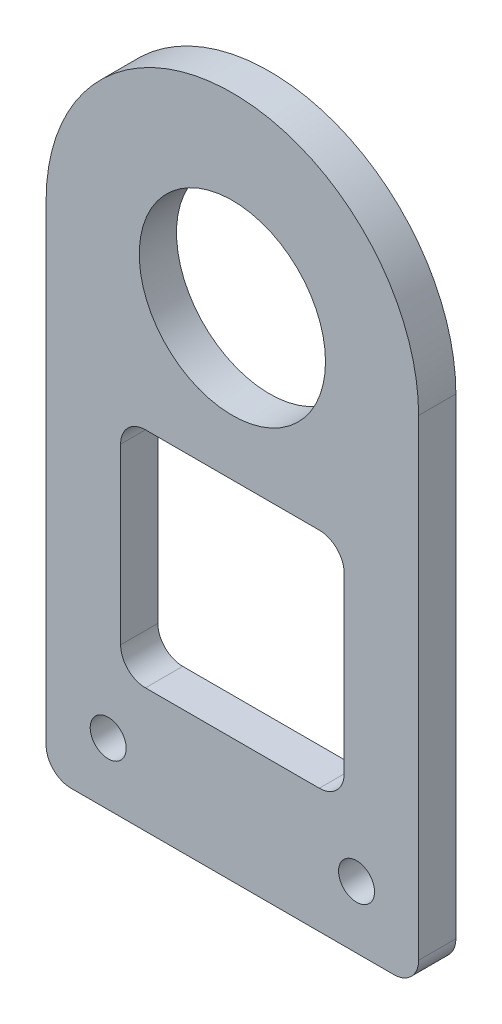
SolidWorks part; units mm, degrees
material "Thornel Mat VMA"
ref_plane "前视基准面" through (0, 0, 0) normal (0, 0, 1) x (1, 0, 0)
ref_plane "上视基准面" through (0, 0, 0) normal (0, 1, 0) x (1, 0, 0)
ref_plane "右视基准面" through (0, 0, 0) normal (1, 0, 0) x (0, 0, -1)
sketch "草图1" plane through (0, 0, 0) normal (0, 0, 1) x (1, 0, 0)
  line L0 (10, 0) -> (-10, 0) construction
  line L1 (0, 0) -> (0, 35) construction
  line L2 (-15, 35) -> (-15, -5)
  line L4 (-9, 5) -> (9, 5)
  line L5 (15, 35) -> (15, -5)
  line L6 (15, -5) -> (-15, -5)
  line L7 (-9, 5) -> (-9, 23)
  line L8 (-9, 23) -> (9, 23)
  line L9 (9, 5) -> (9, 23)
  line L10 (-9, 5) -> (9, 23) construction
  line L11 (-9, 23) -> (9, 5) construction
  circle A0 centre (0, 35) radius 7.5
  circle A1 centre (-10, 0) radius 1.45
  circle A2 centre (10, 0) radius 1.45
  arc A3 (15, 35) -> (-15, 35) centre (0, 35) ccw
  point P4 (0, 0)
  point P10 (0, 14)
  dimension "D1" = 15
  dimension "D2" = 2.9
  dimension "D5" = 30
  dimension "D3" = 20
  dimension "D4" = 35
  dimension "D6" = 5
  dimension "D7" = 5
  dimension "D8" = 12
  dimension "D9" = 6
extrude "凸台-拉伸1" add sketch "草图1" along normal blind 3
fillet "圆角1" radius 2 6 edges at (15, -5, 1.5) (-15, -5, 1.5) (-9, 5, 1.5) (9, 5, 1.5) (9, 23, 1.5) (-9, 23, 1.5)
